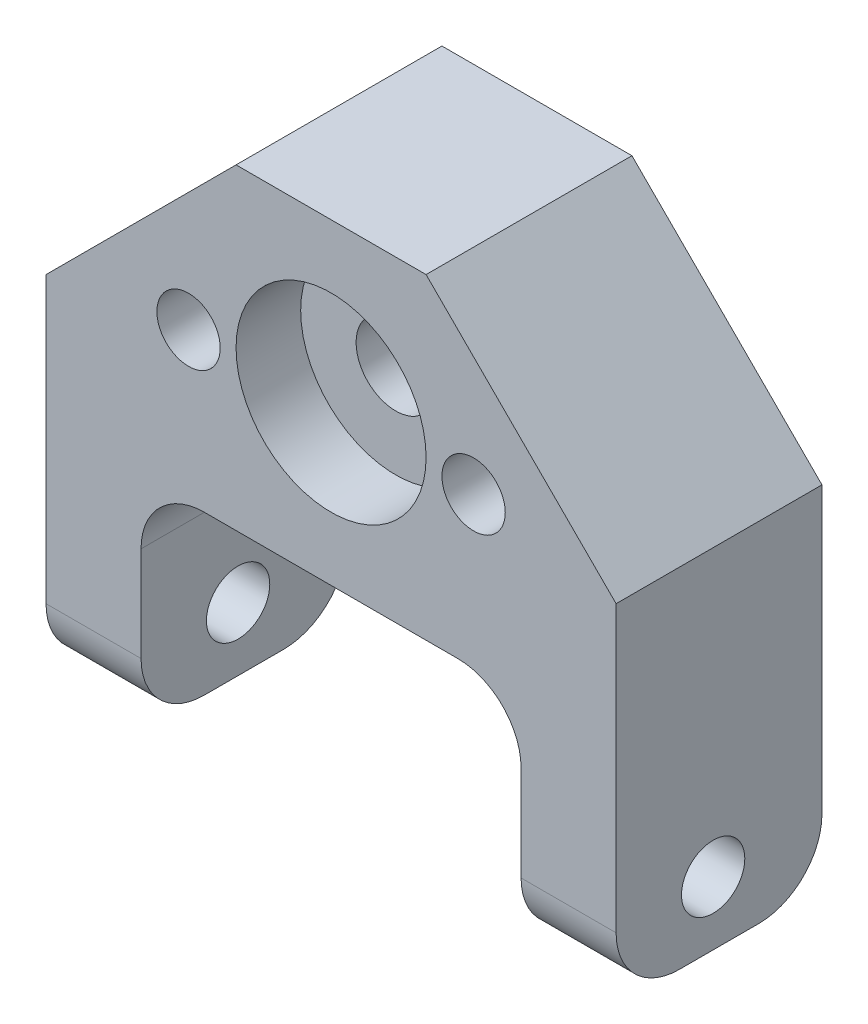
SolidWorks part; units mm, degrees
material "1060 Alloy"
ref_plane "Front" through (0, 0, 0) normal (0, 0, 1) x (1, 0, 0)
ref_plane "Top" through (0, 0, 0) normal (0, 1, 0) x (1, 0, 0)
ref_plane "Right" through (0, 0, 0) normal (1, 0, 0) x (0, 0, -1)
sketch "Sketch1" plane through (0, 0, 0) normal (0, 0, 1) x (1, 0, 0)
  line L1 (28.575, -15.875) -> (-28.575, -15.875)
  line L2 (28.575, -15.875) -> (28.575, 15.875)
  line L3 (28.575, 15.875) -> (-28.575, 15.875)
  line L4 (-28.575, -15.875) -> (-28.575, 15.875)
  line L5 (28.575, -15.875) -> (-28.575, 15.875) construction
  line L6 (28.575, 15.875) -> (-28.575, -15.875) construction
  point P0 (0, 0)
  dimension "D1" = 31.75
  dimension "D2" = 57.15
extrude "Boss-Extrude1" add sketch "Sketch1" along normal blind 20.6375
sketch "Sketch2" plane through (0, 0, 0) normal (0, 0, -1) x (-1, 0, 0)
  circle A0 centre (0, 0) radius 11.1125
  dimension "D1" = 22.225
extrude "Cut-Extrude1" cut sketch "Sketch2" against normal blind 6.985
sketch "Sketch3" plane through (0, 0, 6.985) normal (0, 0, -1) x (-1, 0, 0)
  circle A0 centre (0, 0) radius 8.255
  dimension "D1" = 16.51
extrude "Cut-Extrude2" cut sketch "Sketch3" against normal blind 2.413
sketch "Sketch4" plane through (0, 0, 9.398) normal (0, 0, -1) x (-1, 0, 0)
  circle A0 centre (0, 0) radius 3.9688
  dimension "D1" = 7.9375
extrude "Cut-Extrude3" cut sketch "Sketch4" against normal through all
sketch "Sketch6" plane through (0, 0, 9.398) normal (0, 0, -1) x (-1, 0, 0)
  circle A0 centre (0, 0) radius 9.525
  dimension "D1" = 19.05
extrude "Cut-Extrude4" cut sketch "Sketch6" against normal through all from offset 4.7625 offset against normal yes
sketch "Sketch7" plane through (0, -15.875, 0) normal (0, -1, 0) x (1, 0, 0)
  line L0 (-28.575, 0) -> (28.575, 0) construction
  line L1 (-28.575, 20.6375) -> (-19.05, 20.6375)
  line L2 (-28.575, 20.6375) -> (-28.575, 0)
  line L3 (-28.575, 0) -> (-19.05, 0)
  line L4 (-19.05, 20.6375) -> (-19.05, 0)
  line L6 (28.575, 20.6375) -> (19.05, 20.6375)
  line L7 (28.575, 20.6375) -> (28.575, 0)
  line L8 (28.575, 0) -> (19.05, 0)
  line L9 (19.05, 20.6375) -> (19.05, 0)
  dimension "D1" = 9.525
extrude "Boss-Extrude2" add sketch "Sketch7" along normal blind 22.225
sketch "Sketch9" plane through (28.575, 0, 0) normal (1, 0, 0) x (0, 0, -1)
  line L0 (0, -38.1) -> (-20.6375, -38.1) construction
  circle A0 centre (-10.9095, -31.75) radius 3.175
  dimension "D2" = 6.35
  dimension "D1" = 6.35
extrude "Cut-Extrude5" cut sketch "Sketch9" against normal through all
fillet "Fillet1" radius 6.35 2 edges at (19.05, -15.875, 10.3187) (-19.05, -15.875, 10.3187)
hole_wizard "1/4 (0.2500) Dowel Hole1" positions "Sketch10" profile "Sketch11" hole size "1/4" standard "ANSI Inch"
sketch "Sketch10" plane through (0, 0, 20.6375) normal (0, 0, 1) x (1, 0, 0)
  circle A0 centre (-14.2876, -0.8255) radius 3.175 construction
  circle A3 centre (14.2874, -0.828) radius 3.175 construction
  point P0 (-14.2876, -0.8255)
  point P2 (14.2874, -0.828)
sketch "Sketch11" plane through (-14.2876, -0.8255, 20.6375) normal (1, 0, 0) x (0, -1, 0)
  line L0 (0, 0) -> (0, 11.4327)
  line L1 (0, 11.4327) -> (3.175, 9.525)
  line L2 (3.175, 9.525) -> (3.175, 0)
  line L5 (3.175, 0) -> (0, 0)
  line L10 (0, 11.4327) -> (-3.175, 9.525) construction
  line L11 (0, -6.35) -> (0, 107.95) construction
  dimension "Hole Dia." = 6.35
  dimension "Hole Depth" = 9.525
  dimension "Drill Angle" = 118
fillet "Fillet3" radius 6.35 4 edges at (23.8125, -38.1, 0) (23.8125, -38.1, 20.6375) (-23.8125, -38.1, 20.6375) (-23.8125, -38.1, 0)
chamfer "Chamfer1" distance 19.05 angle 45 2 edges at (28.575, 15.875, 10.3187) (-28.575, 15.875, 10.3187)
